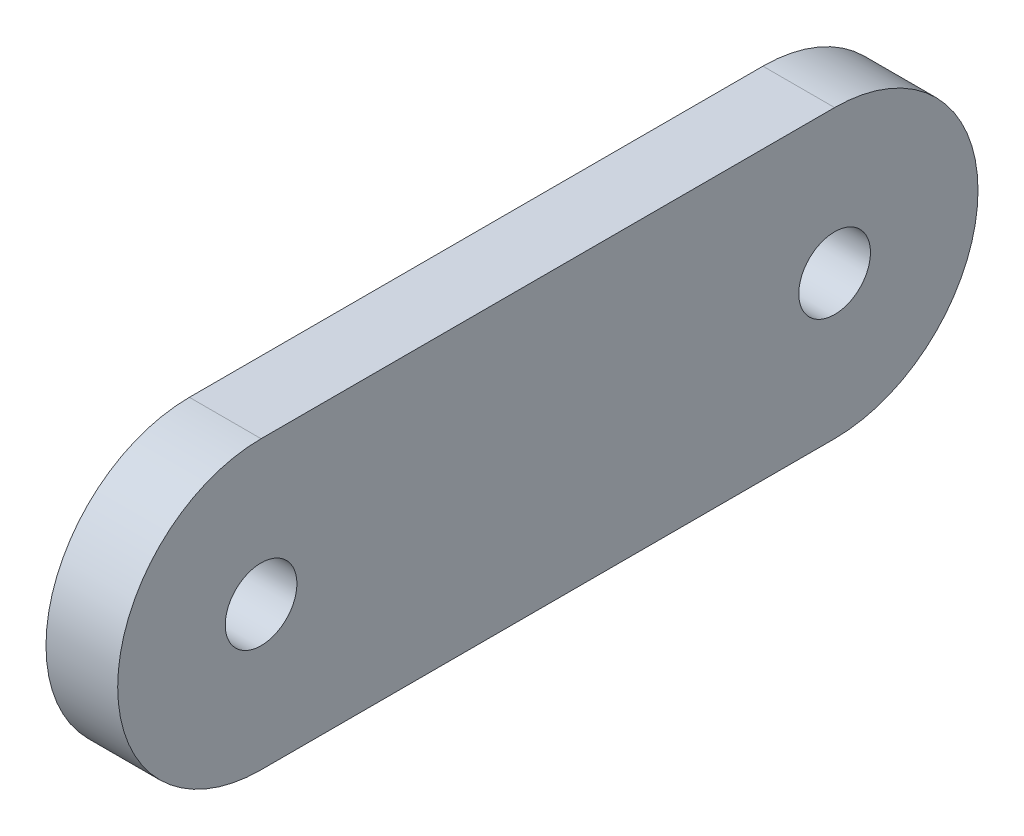
SolidWorks part; units mm, degrees
ref_plane "Front Plane" through (0, 0, 0) normal (0, 0, 1) x (1, 0, 0)
ref_plane "Top Plane" through (0, 0, 0) normal (0, 1, 0) x (1, 0, 0)
ref_plane "Right Plane" through (0, 0, 0) normal (1, 0, 0) x (0, 0, -1)
sketch "Sketch1" plane through (0, 0, 0) normal (1, 0, 0) x (0, 0, -1)
  line L0 (0, 0) -> (40, 0) construction
  line L1 (0, 10) -> (40, 10)
  line L2 (0, -10) -> (40, -10)
  arc A0 (0, 10) -> (0, -10) centre (0, 0) ccw
  arc A1 (40, -10) -> (40, 10) centre (40, 0) ccw
  circle A2 centre (0, 0) radius 2.5
  circle A3 centre (40, 0) radius 2.5
  point P3 (20, 0)
  dimension "D1" = 10
  dimension "D3" = 5
  dimension "D4" = 5
  dimension "D2" = 40
extrude "Boss-Extrude1" add sketch "Sketch1" along normal blind 5
